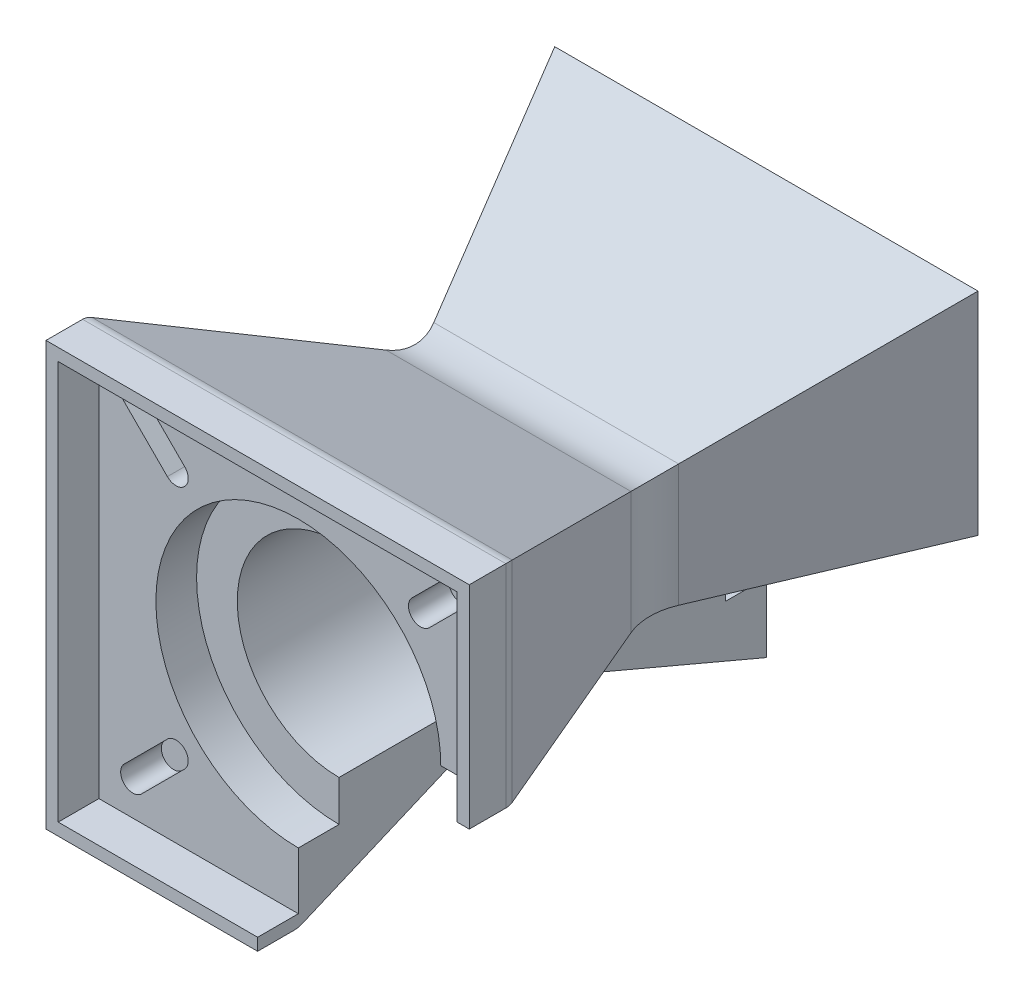
SolidWorks part; units mm, degrees
material "Cast Stainless Steel"
ref_plane "Front Plane" through (0, 0, 0) normal (0, 0, 1) x (1, 0, 0)
ref_plane "Top Plane" through (0, 0, 0) normal (0, 1, 0) x (1, 0, 0)
ref_plane "Right Plane" through (0, 0, 0) normal (1, 0, 0) x (0, 0, -1)
sketch "Sketch1" plane through (0, 0, 0) normal (0, 0, 1) x (1, 0, 0)
  line L1 (-52, 52) -> (52, 52)
  line L2 (-52, 52) -> (-52, -52)
  line L3 (-52, -52) -> (52, -52)
  line L4 (52, 52) -> (52, -52)
  line L5 (-52, 52) -> (52, -52) construction
  line L6 (-52, -52) -> (52, 52) construction
  point P0 (0, 0)
  dimension "D1" = 104
  dimension "D2" = 104
extrude "Boss-Extrude1" add sketch "Sketch1" along normal blind 57.5 draft 23
mirror "Mirror1" about plane through (0, 0, 57.5) normal (0, 0, 1) of bodies 101
sketch "Sketch2" plane through (0, 0, 115) normal (0, 0, 1) x (1, 0, 0)
  circle A0 centre (0, 0) radius 25
  dimension "D1" = 50
extrude "Cut-Extrude1" cut sketch "Sketch2" against normal through all and the other way through all
sketch "Sketch3" plane through (0, 0, 115) normal (0, 0, 1) x (1, 0, 0)
  circle A0 centre (0, 0) radius 35
  dimension "D1" = 70
extrude "Cut-Extrude2" cut sketch "Sketch3" against normal blind 10
ref_plane "Plane1" through (0, 0, 57.5) normal (0, 0, 1) x (1, 0, 0)
mirror "Mirror2" about plane through (0, 0, 57.5) normal (0, 0, 1) of "Cut-Extrude2"
sketch "Sketch4" plane through (0, 0, 115) normal (0, 0, 1) x (1, 0, 0)
  line L1 (0, 0) -> (52, 0)
  line L2 (0, 0) -> (0, -52)
  line L3 (0, -52) -> (52, -52)
  line L4 (52, 0) -> (52, -52)
extrude "Cut-Extrude3" cut sketch "Sketch4" against normal through all
fillet "Fillet1" radius 15 4 edges at (27.5927, 13.7963, 57.5) (0, 27.5927, 57.5) (-27.5927, 0, 57.5) (-13.7963, -27.5927, 57.5)
sketch "Sketch5" plane through (0, 0, 115) normal (0, 0, 1) x (1, 0, 0)
  line L6 (-52, -52) -> (0, -52)
  line L7 (0, -52) -> (0, -35)
  line L8 (35, 0) -> (52, 0)
  line L9 (52, 0) -> (52, 52)
  line L10 (52, 52) -> (-52, 52)
  line L11 (-52, 52) -> (-52, -52)
  line L12 (-52, -52) -> (0, -52)
  line L13 (0, -52) -> (0, -49)
  line L14 (49, 0) -> (52, 0)
  line L15 (52, 0) -> (52, 52)
  line L16 (52, 52) -> (-52, 52)
  line L17 (-52, 52) -> (-52, -52)
  line L24 (-49, -49) -> (-3, -49)
  line L25 (-3, -49) -> (-3, -37.8814)
  line L26 (37.8814, 3) -> (49, 3)
  line L27 (49, 3) -> (49, 49)
  line L28 (49, 49) -> (-49, 49)
  line L29 (-49, 49) -> (-49, -49)
  line L30 (-49, -49) -> (0, -49)
  line L33 (49, 0) -> (49, 49)
  line L34 (49, 49) -> (-49, 49)
  line L35 (-49, 49) -> (-49, -49)
  arc A1 (35, 0) -> (0, -35) centre (0, 0) ccw
  arc A4 (37.8814, 3) -> (-3, -37.8814) centre (0, 0) ccw
  dimension "D1" = 0
  dimension "D2" = 3
extrude "Boss-Extrude3" add sketch "Sketch5" along normal blind 10
fillet "Fillet2" radius 5 4 edges at (52, 26, 115) (0, 52, 115) (-52, 0, 115) (-26, -52, 115)
sketch "Sketch6" plane through (0, 0, 115) normal (0, 0, 1) x (1, 0, 0)
  line L0 (0, 0) -> (-52, 52) construction
  line L1 (-40.6586, 40.6586) -> (-30.052, 30.052) construction
  line L2 (40.6586, 40.6586) -> (30.052, 30.052) construction
  line L3 (-38.5373, 42.78) -> (-27.9307, 32.1734)
  line L4 (-42.78, 38.5373) -> (-32.1734, 27.9307)
  line L5 (42.78, 38.5373) -> (32.1734, 27.9307)
  line L6 (38.5373, 42.78) -> (27.9307, 32.1734)
  line L7 (40.6586, -40.6586) -> (30.052, -30.052) construction
  line L8 (38.5373, -42.78) -> (27.9307, -32.1734)
  line L9 (42.78, -38.5373) -> (32.1734, -27.9307)
  line L10 (-40.6586, -40.6586) -> (-30.052, -30.052) construction
  line L11 (-42.78, -38.5373) -> (-32.1734, -27.9307)
  line L12 (-38.5373, -42.78) -> (-27.9307, -32.1734)
  circle A0 centre (0, 0) radius 50 construction
  arc A1 (-38.5373, 42.78) -> (-42.78, 38.5373) centre (-40.6586, 40.6586) ccw
  arc A2 (-32.1734, 27.9307) -> (-27.9307, 32.1734) centre (-30.052, 30.052) ccw
  arc A3 (42.78, 38.5373) -> (38.5373, 42.78) centre (40.6586, 40.6586) ccw
  arc A4 (27.9307, 32.1734) -> (32.1734, 27.9307) centre (30.052, 30.052) ccw
  arc A5 (38.5373, -42.78) -> (42.78, -38.5373) centre (40.6586, -40.6586) ccw
  arc A6 (32.1734, -27.9307) -> (27.9307, -32.1734) centre (30.052, -30.052) ccw
  arc A7 (-42.78, -38.5373) -> (-38.5373, -42.78) centre (-40.6586, -40.6586) ccw
  arc A8 (-27.9307, -32.1734) -> (-32.1734, -27.9307) centre (-30.052, -30.052) ccw
  point P3 (-35.3553, 35.3553)
  point P8 (0, 0)
  point P9 (0, 0)
  point P10 (-35.3553, 35.3553)
  point P15 (0, 0)
  point P18 (35.3553, 35.3553)
  point P25 (35.3553, -35.3553)
  point P32 (-35.3553, -35.3553)
  point P37 (0, 0)
  point P38 (0, 0)
  point P39 (29.6961, -29.6961)
  point P40 (0, 0)
  point P41 (31.8174, 21.7638)
  point P42 (0, 0)
  dimension "D1" = 100
  dimension "D2" = 3
  dimension "D3" = 15
  dimension "D4" = 4
extrude "Cut-Extrude4" cut sketch "Sketch6" against normal blind 10
equation "\"A\"= 115mm"
equation "\"B\"= 104mm"
equation "\"C\"= 23mm"
